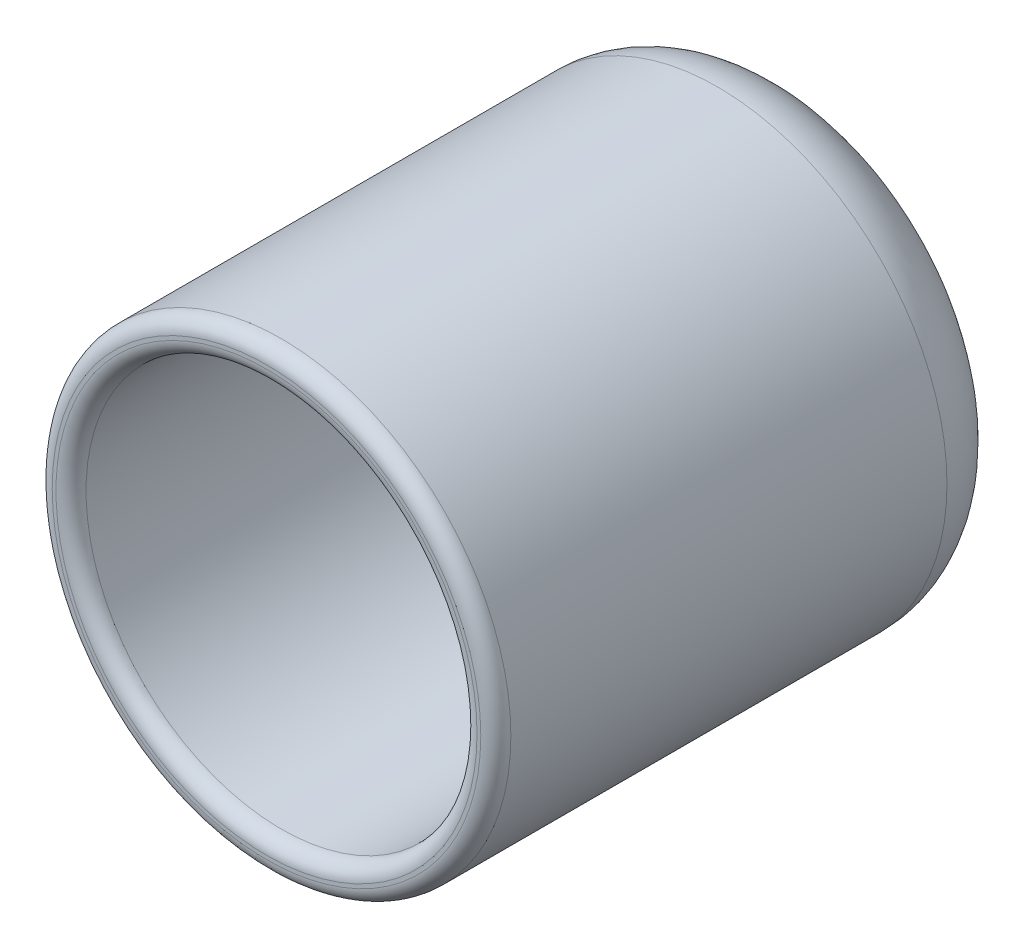
SolidWorks part; units mm, degrees
ref_plane "Front Plane" through (0, 0, 0) normal (0, 0, 1) x (1, 0, 0)
ref_plane "Top Plane" through (0, 0, 0) normal (0, 1, 0) x (1, 0, 0)
ref_plane "Right Plane" through (0, 0, 0) normal (1, 0, 0) x (0, 0, -1)
sketch "Sketch1" plane through (0, 0, 0) normal (0, 0, 1) x (1, 0, 0)
  circle A0 centre (0, 0) radius 3.05
  dimension "D1" = 6.1
extrude "Boss-Extrude1" add sketch "Sketch1" along normal blind 7
sketch "Sketch2" plane through (0, 0, 7) normal (0, 0, 1) x (1, 0, 0)
  circle A0 centre (0, 0) radius 2.6
  circle A1 centre (0, 0) radius 3.05 construction
  dimension "D1" = 5.2
  dimension "D2" = 0.45
extrude "Cut-Extrude1" cut sketch "Sketch2" against normal blind 6.5
fillet "Fillet1" radius 0.2 2 edges at (2.6, 0, 7) (3.05, 0, 7)
fillet "Fillet2" radius 1 1 edges at (3.05, 0, 0)
